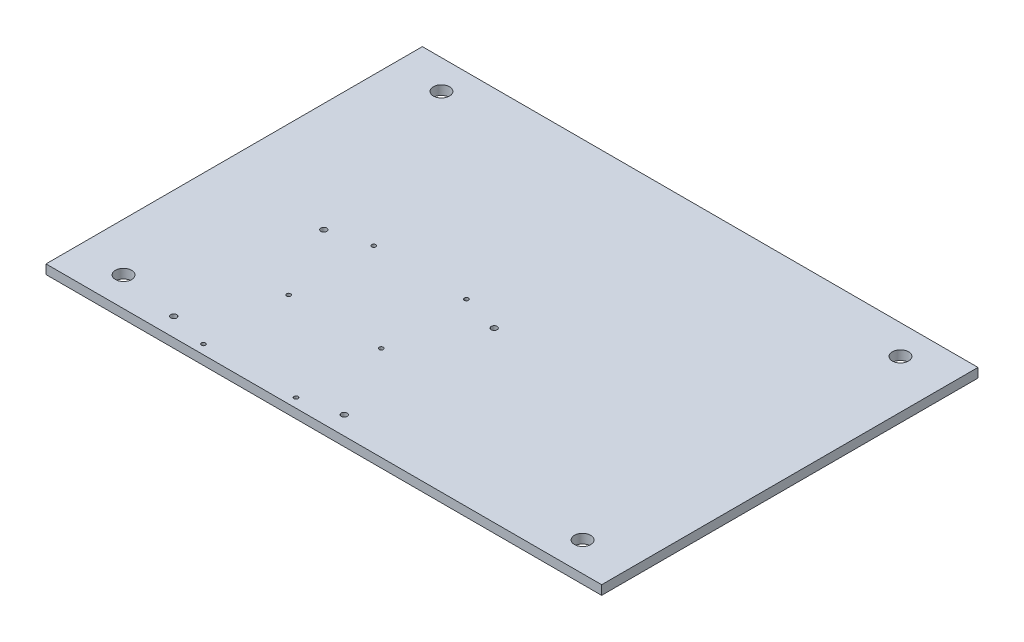
SolidWorks part; units mm, degrees
ref_plane "Front Plane" through (0, 0, 0) normal (0, 0, 1) x (1, 0, 0)
ref_plane "Top Plane" through (0, 0, 0) normal (0, 1, 0) x (1, 0, 0)
ref_plane "Right Plane" through (0, 0, 0) normal (1, 0, 0) x (0, 0, -1)
sketch "Sketch1" plane through (0, 0, 0) normal (0, 1, 0) x (1, 0, 0)
  line L1 (0, 0) -> (300, 0)
  line L2 (0, 0) -> (0, -203.2)
  line L3 (0, -203.2) -> (300, -203.2)
  line L4 (300, 0) -> (300, -203.2)
  dimension "D1" = 203.2
  dimension "D2" = 300
extrude "Boss-Extrude1" add sketch "Sketch1" along normal blind 5
sketch "Sketch2" plane through (0, 5, 0) normal (0, 1, 0) x (1, 0, 0)
  line L0 (150, 0) -> (150, -203.2) construction
  line L1 (300, 0) -> (0, 0) construction
  line L2 (0, -203.2) -> (300, -203.2) construction
  line L3 (0, -101.6) -> (300, -101.6) construction
  line L4 (0, 0) -> (0, -203.2) construction
  line L5 (300, -203.2) -> (300, 0) construction
  circle A0 centre (26.0861, -15.7861) radius 3.2639
  circle A1 centre (273.9139, -15.7861) radius 3.2639
  circle A2 centre (273.9139, -187.4139) radius 3.2639
  circle A3 centre (26.0861, -187.4139) radius 3.2639
  dimension "D1" = 6.5278
  dimension "D2" = 82.55
  dimension "D3" = 120.65
extrude "holes for mounting to chamber" cut sketch "Sketch2" against normal through all contours A0 | A3 | A1 | A2
sketch "locations for led holes" plane through (0, 5, 0) normal (0, 1, 0) x (1, 0, 0)
  line L1 (0, -203.2) -> (300, -203.2) construction
  line L2 (0, 0) -> (0, -203.2) construction
  point P0 (80, -198.2)
  point P1 (80, -152.2)
  point P2 (80, -106.2)
  point P3 (130, -106.2)
  point P4 (130, -152.2)
  point P5 (130, -198.2)
  dimension "D1" = 46
  dimension "D2" = 46
  dimension "D3" = 50
  dimension "D4" = 5
  dimension "D5" = 80
hole_wizard "clearance holes for led panel" positions "Sketch4" profile "Sketch5" hole size "M2" standard "ISO" end condition through all
sketch "Sketch4" plane through (0, 5, 0) normal (0, 1, 0) x (1, 0, 0)
  point P0 (80, -106.2)
  point P3 (130, -106.2)
  point P6 (130, -152.2)
  point P9 (80, -152.2)
  point P12 (80, -198.2)
  point P15 (130, -198.2)
sketch "Sketch5" plane through (80, 5, 106.2) normal (1, 0, 0) x (0, 0, 1)
  line L0 (0, 0) -> (0, 5)
  line L1 (0, 5) -> (1.1, 5)
  line L2 (1.1, 5) -> (1.1, 0)
  line L5 (1.1, 0) -> (0, 0)
  line L11 (0, -6.35) -> (0, 107.95) construction
  dimension "Thru Hole Dia." = 2.2
  dimension "Thru Hole Depth" = 5
sketch "location of holes for solar mount" plane through (0, 5, 0) normal (0, 1, 0) x (1, 0, 0)
  line L0 (0, -203.2) -> (300, -203.2) construction
  line L2 (0, 0) -> (0, -203.2) construction
  point P0 (59, -193.2)
  point P1 (151, -193.2)
  point P2 (151, -112.2)
  point P3 (59, -112.2)
  dimension "D1" = 92
  dimension "D2" = 81
  dimension "D3" = 10
  dimension "D4" = 59
hole_wizard "M3 Clearance Hole1" positions "Sketch7" profile "Sketch8" hole size "M3" standard "ISO" end condition through all
sketch "Sketch7" plane through (0, 5, 0) normal (0, 1, 0) x (1, 0, 0)
  point P0 (59, -112.2)
  point P3 (151, -112.2)
  point P6 (151, -193.2)
  point P9 (59, -193.2)
sketch "Sketch8" plane through (59, 5, 112.2) normal (1, 0, 0) x (0, 0, 1)
  line L0 (0, 0) -> (0, 5)
  line L1 (0, 5) -> (1.6, 5)
  line L2 (1.6, 5) -> (1.6, 0)
  line L5 (1.6, 0) -> (0, 0)
  line L11 (0, -6.35) -> (0, 107.95) construction
  dimension "Thru Hole Dia." = 3.2
  dimension "Thru Hole Depth" = 5
hole_wizard "Hole for 1/4 300® SC Nuts (SP)1" positions "Sketch9" profile "Sketch10" hole size "1/4-20" standard "PEM® Inch"
sketch "Sketch9" plane through (0, 5, 0) normal (0, 1, 0) x (1, 0, 0)
  point P0 (26.0861, -15.7861)
  point P3 (273.9139, -15.7861)
  point P6 (273.9139, -187.4139)
  point P9 (26.0861, -187.4139)
sketch "Sketch10" plane through (26.0861, 5, 15.7861) normal (1, 0, 0) x (0, 0, 1)
  line L0 (0, 0) -> (0, 34.375)
  line L1 (0, 34.375) -> (4.3688, 31.75)
  line L2 (4.3688, 31.75) -> (4.3688, 0)
  line L5 (4.3688, 0) -> (0, 0)
  line L10 (0, 34.375) -> (-4.3688, 31.75) construction
  line L11 (0, -6.35) -> (0, 107.95) construction
  dimension "Hole Dia." = 8.7376
  dimension "Hole Depth" = 31.75
  dimension "Drill Angle" = 118
